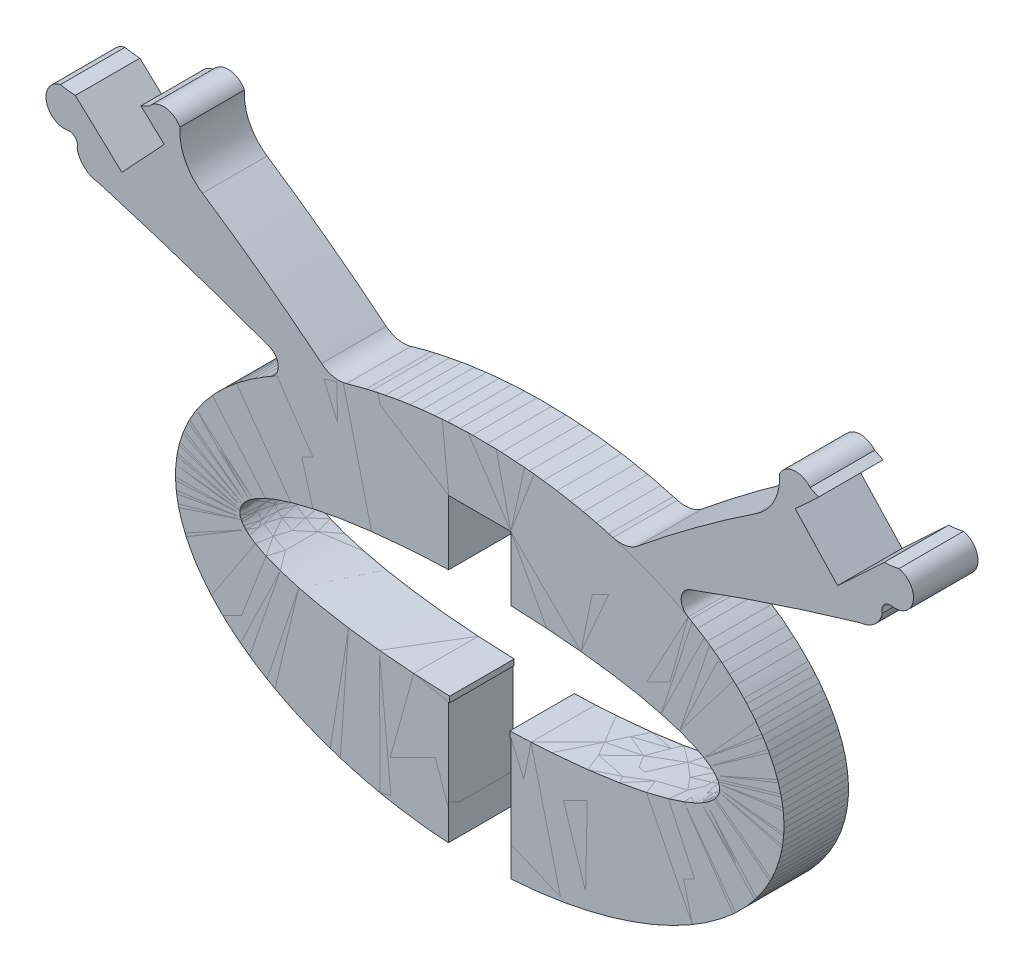
SolidWorks part; units mm, degrees
material "Acrylic (Medium-high impact)"
ref_plane "Front Plane" through (0, 0, 0) normal (0, 0, 1) x (1, 0, 0)
ref_plane "Top Plane" through (0, 0, 0) normal (0, 1, 0) x (1, 0, 0)
ref_plane "Right Plane" through (0, 0, 0) normal (1, 0, 0) x (0, 0, -1)
sketch "스케치1" plane through (0, 0, 0) normal (0, 0, 1) x (1, 0, 0)
  line L0 (0, 10.85) -> (0, 0) construction
  line L7 (0, 0) -> (0, -5.267) construction
  line L8 (-1.4756, -8.4667) -> (1.1169, -8.4667) construction
  line L10 (-1.4756, -2.0674) -> (1.4756, -2.0674) construction
  line L12 (-1.4756, -8.4667) -> (1.4756, -2.0674) construction
  line L13 (-1.4756, -2.0674) -> (1.1169, -8.4667) construction
  line L15 (-1.875, 1.7135) -> (1.875, 1.7135) construction
  line L17 (0, -5.4393) -> (0, 0) construction
  line L18 (-1.4475, 2.54) -> (1.4475, 2.54) construction
  line L19 (-13.5575, -8.4667) -> (13.5575, -8.4667) construction
  line L23 (-13.5575, -8.4667) -> (13.5575, 7.3868) construction
  line L24 (-13.5575, 7.3868) -> (13.5575, -8.4667) construction
  line L26 (-1.4475, 2.54) -> (-1.4475, 5.54)
  line L27 (-1.4475, 5.54) -> (1.4475, 5.54)
  line L28 (1.4475, 2.54) -> (1.4475, 5.54)
  line L29 (-1.4475, 2.54) -> (1.4475, 5.54) construction
  line L30 (-1.4475, 5.54) -> (1.4475, 2.54) construction
  line L31 (-1.5, -8.54) -> (1.5, -8.54) construction
  line L32 (-1.4019, -8.4982) -> (-1.4019, -2.5413)
  line L33 (-1.4019, -2.5413) -> (1.4019, -2.5413) construction
  line L34 (1.4019, -8.4982) -> (1.4019, -2.5413)
  line L35 (-1.5, -8.54) -> (1.4019, -2.5413) construction
  line L36 (-1.4019, -2.5413) -> (1.5, -8.54) construction
  circle A0 centre (0, 0) radius 8.54 construction
  circle A1 centre (0, 0) radius 2.54 construction
  arc A2 (-1.4756, -8.4667) -> (1.1169, -8.4667) centre (-0.1794, 1.3598) cw construction
  ellipse E0 centre (0, 0) end of major axis (-14.1889, 0) minor radius 8.54 (1.4019, -8.4982) -> (-1.4019, -8.4982) ccw
  ellipse E1 centre (0, 0) end of major axis (-11.1889, 0) minor radius 2.5615 (-1.4475, 2.54) -> (-1.4019, -2.5413) ccw
  ellipse E2 centre (0, 0) end of major axis (-11.1889, 0) minor radius 2.5615 (1.4019, -2.5413) -> (1.4475, 2.54) ccw
  point P2 (0, 10.85)
  point P5 (0, 2.8708)
  point P7 (0, 4.04)
  point P10 (-0.0955, -5.4741)
  point P30 (0, -5.4393)
  dimension "D1" = 6
  dimension "D2" = 5.08
  dimension "D6" = 2.895
  dimension "D3" = 3
  dimension "D4" = 3
  dimension "D5" = 2.5925
  dimension "D7" = 3
  dimension "D8" = 3
extrude "보스-돌출1" add sketch "스케치1" along normal blind 3
sketch "스케치2" plane through (0, 0, 3) normal (0, 0, 1) x (1, 0, 0)
  line L0 (0, 0) -> (0, 8.54) construction
  ellipse E0 centre (0, 0) end of major axis (-14.1889, 0) minor radius 8.54 (1.4019, -8.4982) -> (-1.4019, -8.4982) ccw construction
sketch "스케치3" plane through (0, 0, 3) normal (0, 0, 1) x (1, 0, 0)
  line L0 (0, 0) -> (0, 9.81) construction
  line L6 (1.4475, 5.54) -> (1.4475, 2.54)
  line L7 (1.4019, -2.5413) -> (1.4019, -8.4982)
  line L8 (-1.4019, -8.4982) -> (-1.4019, -2.5413)
  line L9 (-1.4475, 2.54) -> (-1.4475, 5.54)
  line L10 (-1.4475, 5.54) -> (1.4475, 5.54)
  line L11 (1.4475, 5.54) -> (1.4475, 2.54)
  line L12 (1.4019, -2.5413) -> (1.4019, -8.4982)
  line L13 (-1.4019, -8.4982) -> (-1.4019, -2.5413)
  line L14 (-1.4475, 2.54) -> (-1.4475, 5.54)
  line L15 (-1.4475, 5.54) -> (1.4475, 5.54)
  arc A0 (-6.8511, 7.4785) -> (-16.4356, 12.6393) centre (-17.9807, -1.7106) ccw construction
  arc A1 (-8.4526, 6.8592) -> (-16.2168, 9.1811) centre (-17.1042, -7.9288) ccw construction
  arc A2 (-16.4356, 12.6393) -> (-16.2168, 9.1811) centre (-18.4411, 10.7764) ccw construction
  arc A3 (8.4526, 6.8592) -> (17.7872, 10.0095) centre (52.0147, -106.8159) cw
  arc A4 (6.8511, 7.4785) -> (12.9294, 12.0082) centre (51.8507, -46.562) cw
  arc A5 (16.4356, 12.6393) -> (16.2168, 9.1811) centre (18.4411, 10.7764) cw construction
  arc A6 (-8.4526, 6.8592) -> (-17.7872, 10.0095) centre (-52.0147, -106.8159) ccw
  arc A7 (-6.8511, 7.4785) -> (-12.9294, 12.0082) centre (-51.8507, -46.562) ccw
  arc A13 (-13.9826, 14.1517) -> (-12.9294, 12.0082) centre (-11.6165, 13.9838) ccw
  arc A22 (-18.4455, 13.0034) -> (-19.5529, 13.0889) centre (-18.7311, 16.52) cw
  arc A23 (-19.5529, 13.0889) -> (-19.1963, 11.4121) centre (-19.3731, 12.2508) ccw
  arc A24 (-19.1963, 11.4121) -> (-18.7779, 10.8959) centre (-19.1527, 11.0198) cw
  arc A26 (-18.4455, 13.0034) -> (-15.4088, 14.2923) centre (-28.3584, 40.5798) ccw
  arc A27 (-15.4088, 14.2923) -> (-13.9826, 14.1517) centre (-14.7432, 13.7406) cw
  arc A28 (15.4088, 14.2923) -> (13.9826, 14.1517) centre (14.7432, 13.7406) ccw
  arc A29 (18.4455, 13.0034) -> (15.4088, 14.2923) centre (28.3584, 40.5798) cw
  arc A31 (19.1963, 11.4121) -> (18.7779, 10.8959) centre (19.1527, 11.0198) ccw
  arc A32 (19.5529, 13.0889) -> (19.1963, 11.4121) centre (19.3731, 12.2508) cw
  arc A33 (18.4455, 13.0034) -> (19.5529, 13.0889) centre (18.7311, 16.52) ccw
  arc A34 (13.9826, 14.1517) -> (12.9294, 12.0082) centre (11.6165, 13.9838) cw
  arc A35 (-18.7779, 10.8959) -> (-17.7872, 10.0095) centre (-17.6852, 11.1203) ccw
  arc A36 (18.7779, 10.8959) -> (17.7872, 10.0095) centre (17.6852, 11.1203) cw
  ellipse E0 centre (0, 0) end of major axis (-14.1889, 0) minor radius 8.54 (1.4019, -8.4982) -> (-1.4019, -8.4982) ccw construction
  ellipse E1 centre (0, 0) end of major axis (-14.1889, 0) minor radius 8.54 (-8.4526, 6.8592) -> (-1.4019, -8.4982) ccw
  ellipse E2 centre (0, 0) end of major axis (-14.1889, 0) minor radius 8.54 (6.8511, 7.4785) -> (-6.8511, 7.4785) ccw
  ellipse E4 centre (0, 0) end of major axis (-11.1889, 0) minor radius 2.5615 (1.4019, -2.5413) -> (1.4475, 2.54) ccw
  ellipse E5 centre (0, 0) end of major axis (-14.1889, 0) minor radius 8.54 (1.4019, -8.4982) -> (-1.4019, -8.4982) ccw
  ellipse E6 centre (0, 0) end of major axis (-11.1889, 0) minor radius 2.5615 (-1.4475, 2.54) -> (-1.4019, -2.5413) ccw
  ellipse E7 centre (0, 0) end of major axis (-11.1889, 0) minor radius 2.5615 (1.4019, -2.5413) -> (1.4475, 2.54) ccw
  ellipse E8 centre (0, 0) end of major axis (-14.1889, 0) minor radius 8.54 (1.4019, -8.4982) -> (8.4526, 6.8592) ccw
  ellipse E9 centre (0, 0) end of major axis (-11.1889, 0) minor radius 2.5615 (-1.4475, 2.54) -> (-1.4019, -2.5413) ccw
  dimension "D1" = 0
extrude "보스-돌출2" add sketch "스케치3" against normal blind 3.01 separate body
sketch "스케치4" plane through (0, 0, -0.01) normal (0, 0, -1) x (-1, 0, 0)
  line L0 (-16.6902, 10.971) -> (-14.7167, 13.0891)
  line L1 (-16.6902, 10.971) -> (-18.8851, 13.016)
  line L2 (-14.7167, 13.0891) -> (-16.9117, 15.1341)
  line L3 (-18.8851, 13.016) -> (-16.9117, 15.1341)
  line L4 (-16.6902, 10.971) -> (-16.9117, 15.1341) construction
  line L5 (-14.7167, 13.0891) -> (-18.8851, 13.016) construction
  line L6 (0, 0) -> (0, 8.54) construction
  line L7 (0, 0) -> (0, 8.54) construction
  line L8 (14.7167, 13.0891) -> (16.9117, 15.1341)
  line L9 (18.8851, 13.016) -> (16.9117, 15.1341)
  line L10 (16.6902, 10.971) -> (18.8851, 13.016)
  line L11 (16.6902, 10.971) -> (14.7167, 13.0891)
  point P1 (-16.8009, 13.0525)
  dimension "D1" = 2.895
  dimension "D2" = 3
  dimension "D3" = 47.025
extrude "컷-돌출1" cut sketch "스케치4" against normal up to surface (3.01 mm away) up to face at (0, 7.815, 3)
sketch "스케치5" plane through (0, 0, 3) normal (0, 0, 1) x (1, 0, 0)
  line L0 (0, 0) -> (0, -6.4953) construction
  line L1 (-1.4625, -10.1791) -> (1.4625, -10.1791)
  line L2 (-1.4625, -10.1791) -> (-1.4625, -2.8114)
  line L3 (-1.4625, -2.8114) -> (1.4625, -2.8114)
  line L4 (1.4625, -10.1791) -> (1.4625, -2.8114)
  line L5 (-1.4625, -10.1791) -> (1.4625, -2.8114) construction
  line L6 (-1.4625, -2.8114) -> (1.4625, -10.1791) construction
  point P0 (0, -6.4953)
  dimension "D1" = 2.925
extrude "컷-돌출2" cut sketch "스케치5" against normal up to surface (3.01 mm away)
fillet "필렛1" radius 1.27 4 edges at (-6.8511, 7.4785, 1.495) (6.8511, 7.4785, 1.495) (-1.4625, -8.4945, 1.495) (1.4625, -8.4945, 1.495)
fillet "필렛2" radius 0.635 2 edges at (8.4526, 6.8592, 1.495) (-8.4526, 6.8592, 1.495)
